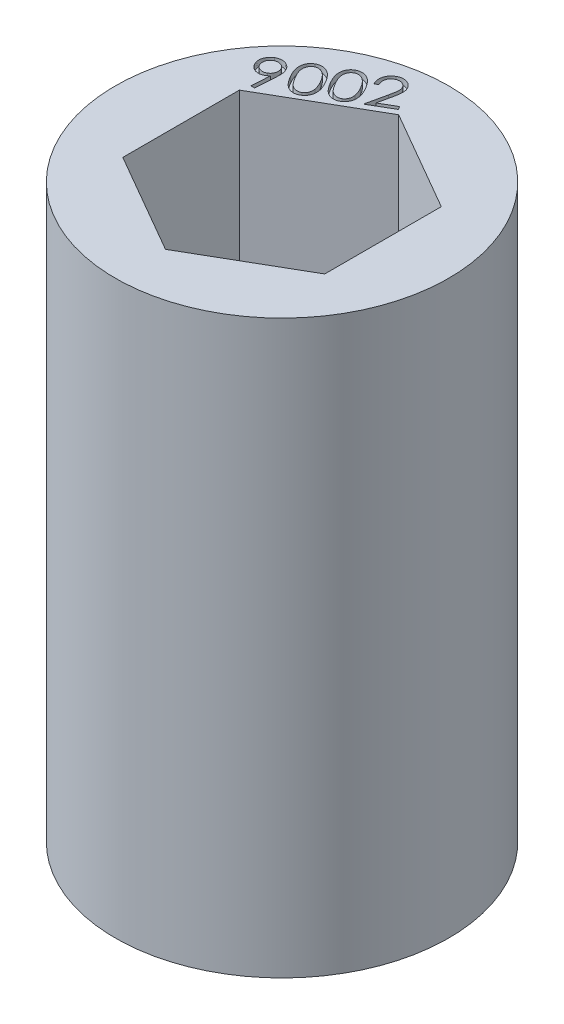
SolidWorks part; units mm, degrees
material "ABS"
ref_plane "Front Plane" through (0, 0, 0) normal (0, 0, 1) x (1, 0, 0)
ref_plane "Top Plane" through (0, 0, 0) normal (0, 1, 0) x (1, 0, 0)
ref_plane "Right Plane" through (0, 0, 0) normal (1, 0, 0) x (0, 0, -1)
sketch "Sketch1" plane through (0, 0, 0) normal (0, 1, 0) x (1, 0, 0)
  line L1 (0, 7.7723) -> (-6.731, 3.8861)
  line L2 (-6.731, 3.8861) -> (-6.731, -3.8861)
  line L3 (-6.731, -3.8861) -> (0, -7.7723)
  line L4 (0, -7.7723) -> (6.731, -3.8861)
  line L5 (6.731, -3.8861) -> (6.731, 3.8861)
  line L6 (6.731, 3.8861) -> (0, 7.7723)
  circle A0 centre (0, 0) radius 11.1125
  circle A1 centre (0, 0) radius 6.731 construction
  dimension "D1" = 22.225
  dimension "D2" = 13.462
extrude "Boss-Extrude1" add sketch "Sketch1" along normal blind 38.1
sketch "Sketch2" plane through (0, 38.1, 0) normal (0, 1, 0) x (1, 0, 0)
  line L0 (-6.9548, 4.2262) -> (-0.2212, 8.1139) construction
  line L2 (0, 7.7723) -> (-6.731, 3.8861) construction
  text T0 "9002" font "Century Gothic" height 2.54
  dimension "D1" = 0.4064
extrude "Cut-Extrude2" cut sketch "Sketch2" against normal blind 0.4
